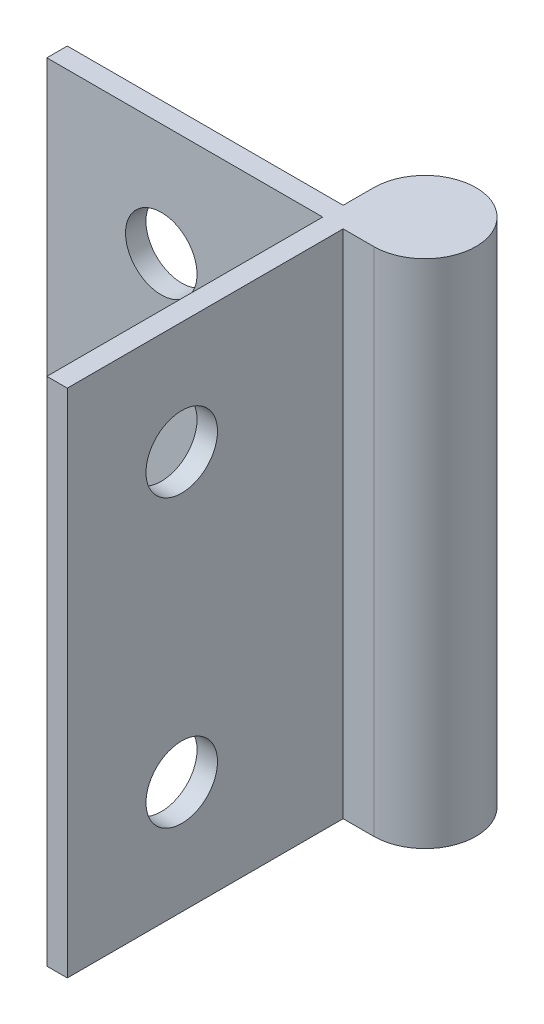
SolidWorks part; units mm, degrees
ref_plane "前视基准面" through (0, 0, 0) normal (0, 0, 1) x (1, 0, 0)
ref_plane "上视基准面" through (0, 0, 0) normal (0, 1, 0) x (1, 0, 0)
ref_plane "右视基准面" through (0, 0, 0) normal (1, 0, 0) x (0, 0, -1)
other "Configuration Table"
sketch "草图1" plane through (0, 0, 0) normal (0, 1, 0) x (1, 0, 0)
  line L1 (0, -2.5) -> (-16, -2.5)
  line L2 (0, -2.5) -> (0, -1.5)
  line L3 (0, -1.5) -> (-16, -1.5)
  line L4 (-16, -2.5) -> (-16, -1.5)
  line L5 (-1.5, 0) -> (-2.5, 0)
  line L6 (-1.5, 0) -> (-1.5, -16)
  line L7 (-1.5, -16) -> (-2.5, -16)
  line L8 (-2.5, 0) -> (-2.5, -16)
  circle A0 centre (0, 0) radius 2.5
  circle A1 centre (0, 0) radius 1.5
  dimension "D3" = 5
  dimension "D4" = 1
  dimension "D1" = 1
  dimension "D2" = 16
  dimension "D5" = 16
extrude "凸台-拉伸1" add sketch "草图1" along normal mid plane 25 contours L8 L3 L4 L1 | L1 L8 L7 L6 | A0 L3 L8 L1 L6 | A0 L6 L1 | L6 A0 L2 L3 | A1 L2 A0 L5
sketch "草图4" plane through (0, 12.5, 0) normal (0, 1, 0) x (1, 0, 0)
  circle A0 centre (0, 0) radius 2.1213
extrude "凸台-拉伸3" add sketch "草图4" against normal blind 25
sketch "草图5" plane through (0, 0, 1.5) normal (0, 0, -1) x (-1, 0, 0)
  line L0 (10.4, -7) -> (10.4, 7) construction
  circle A0 centre (10.4, -7) radius 1.75
  circle A1 centre (10.4, 7) radius 1.75
  point P4 (10.4, 0)
  dimension "D2" = 3.5
  dimension "D1" = 14
  dimension "D3" = 10.4
extrude "切除-拉伸1" cut sketch "草图5" against normal blind 1
sketch "草图6" plane through (-1.5, 0, 0) normal (1, 0, 0) x (0, 0, -1)
  line L0 (-10.4, 7) -> (-10.4, -7) construction
  circle A0 centre (-10.4, -7) radius 1.75
  circle A1 centre (-10.4, 7) radius 1.75
  point P4 (-10.4, 0)
  dimension "D2" = 3.5
  dimension "D1" = 14
  dimension "D3" = 10.4
extrude "切除-拉伸2" cut sketch "草图6" against normal blind 1
